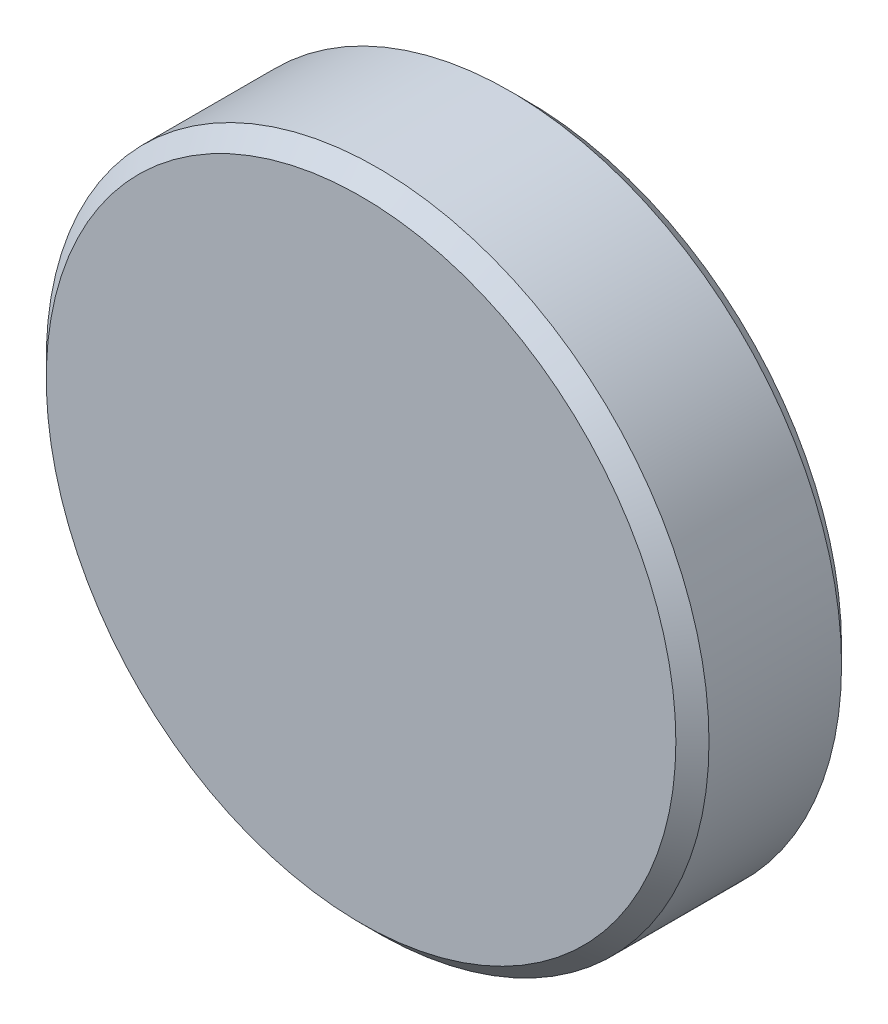
SolidWorks part; units mm, degrees
ref_plane "前视基准面" through (0, 0, 0) normal (0, 0, 1) x (1, 0, 0)
ref_plane "上视基准面" through (0, 0, 0) normal (0, 1, 0) x (1, 0, 0)
ref_plane "右视基准面" through (0, 0, 0) normal (1, 0, 0) x (0, 0, -1)
sketch "草图1" plane through (0, 0, 0) normal (0, 0, 1) x (1, 0, 0)
  line L0 (-113.5197, 0) -> (102.3608, 0) construction
  line L1 (0, 93.3479) -> (0, -79.614) construction
  circle A0 centre (0, 0) radius 4
  dimension "D1" = 8
extrude "拉伸1" add sketch "草图1" along normal blind 2
chamfer "倒角1" distance 0.2 angle 45 2 edges at (4, 0, 2) (4, 0, 0)
